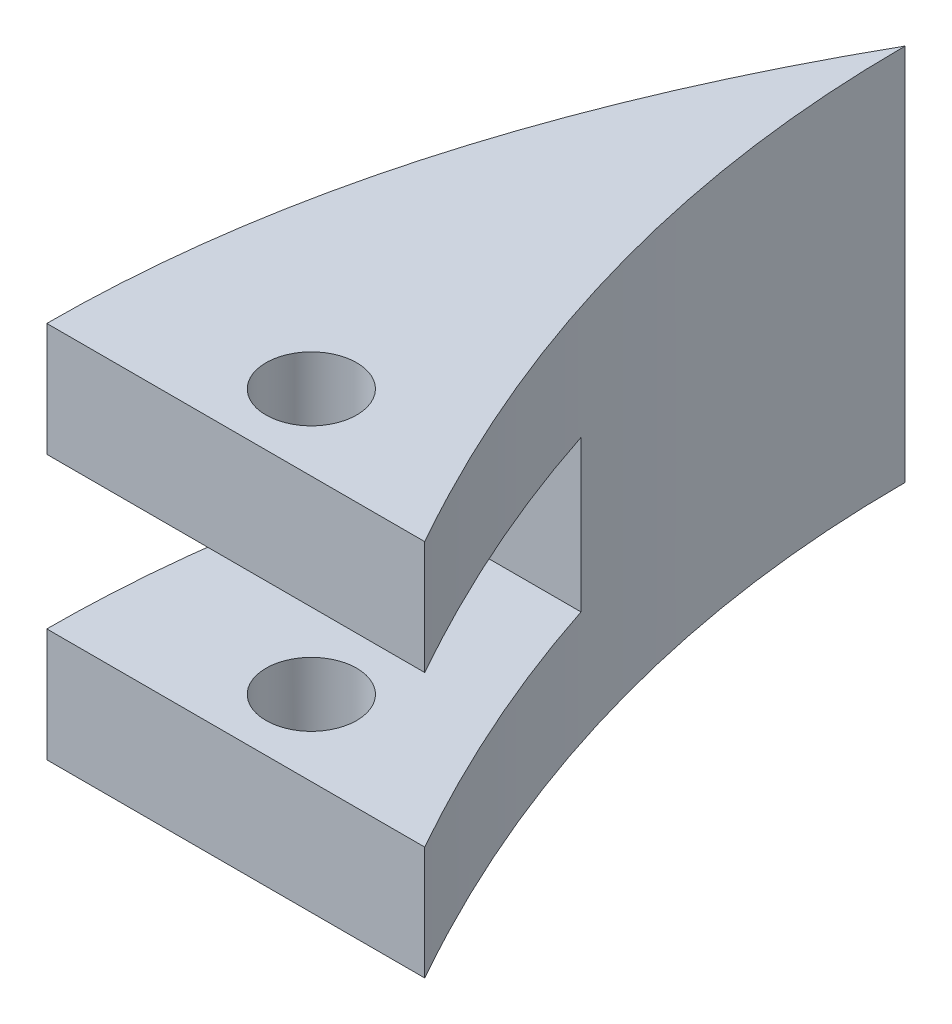
SolidWorks part; units mm, degrees
ref_plane "정면" through (0, 0, 0) normal (0, 0, 1) x (1, 0, 0)
ref_plane "윗면" through (0, 0, 0) normal (0, 1, 0) x (1, 0, 0)
ref_plane "우측면" through (0, 0, 0) normal (1, 0, 0) x (0, 0, -1)
sketch "스케치1" plane through (0, 0, 0) normal (0, 0, 1) x (1, 0, 0)
  line L1 (-12.5, -12.5) -> (12.5, -12.5)
  line L2 (-12.5, -12.5) -> (-12.5, 12.5)
  line L3 (-12.5, 12.5) -> (12.5, 12.5)
  line L4 (12.5, -12.5) -> (12.5, 12.5)
  line L5 (-12.5, -12.5) -> (12.5, 12.5) construction
  line L6 (-12.5, 12.5) -> (12.5, -12.5) construction
  point P0 (0, 0)
  dimension "D1" = 25
extrude "보스-돌출1" add sketch "스케치1" along normal blind 44.2842 contours L3 L4 L1 L2
sketch "스케치2" plane through (0, 12.5, 0) normal (0, 1, 0) x (1, 0, 0)
  line L0 (-12.5, -44.2842) -> (12.5, -44.2842) construction
  circle A0 centre (0, -39.2842) radius 3
  dimension "D1" = 6
  dimension "D2" = 5
extrude "컷-돌출1" cut sketch "스케치2" against normal blind 36.3445 contours A0
sketch "스케치4" plane through (0, 0, 44.2842) normal (0, 0, 1) x (1, 0, 0)
  line L0 (-12.5, -12.5) -> (-12.5, 12.5) construction
  line L1 (12.5, -5) -> (-12.5, -5)
  line L2 (12.5, -5) -> (12.5, 5)
  line L3 (12.5, 5) -> (-12.5, 5)
  line L4 (-12.5, -5) -> (-12.5, 5)
  line L5 (12.5, -5) -> (-12.5, 5) construction
  line L6 (12.5, 5) -> (-12.5, -5) construction
  point P0 (0, 0)
  dimension "D1" = 10
extrude "컷-돌출2" cut sketch "스케치4" against normal blind 18.6398
sketch "스케치5" plane through (0, 12.5, 0) normal (0, 1, 0) x (1, 0, 0)
  line L0 (-12.5, 0) -> (12.5, 0) construction
  line L1 (0, 0) -> (-12.5, -22.1421) construction
  line L4 (-12.5, -22.1421) -> (-12.5, -44.2842) construction
  line L6 (0, 0) -> (-0.0131, -22.059) construction
  line L11 (-0.0131, -22.059) -> (12.5, -44.2842) construction
  line L12 (12.5, -44.2842) -> (12.5, 0)
  line L13 (12.5, 0) -> (-12.5, 0)
  line L14 (-12.5, 0) -> (-12.5, -44.2842)
  spline S0 degree 2 poles (0, 0) (-12.5, -22.1421) (-12.5, -44.2842) knots 0 0 0 1 1 1
  spline S1 degree 2 poles (0, 0) (-0.0131, -22.059) (12.5, -44.2842) knots 0 0 0 1 1 1
  point P7 (0, 0)
  point P9 (0, 0)
  point P10 (12.5, -44.2842)
  point P11 (0, 0)
  point P13 (-12.5, -44.2842)
  point P14 (12.5, -44.2842)
  point P15 (12.5, -44.2842)
  point P16 (0, 0)
  line M2 (12.5, 0) -> (-12.5, 0)
  line M3 (-12.5, 0) -> (-12.5, -44.2842)
  line M5 (12.5, -44.2842) -> (12.5, 0)
extrude "컷-돌출4" cut sketch "스케치5" against normal blind 30 contours S1 M2 M5 | S0 L13 M3
